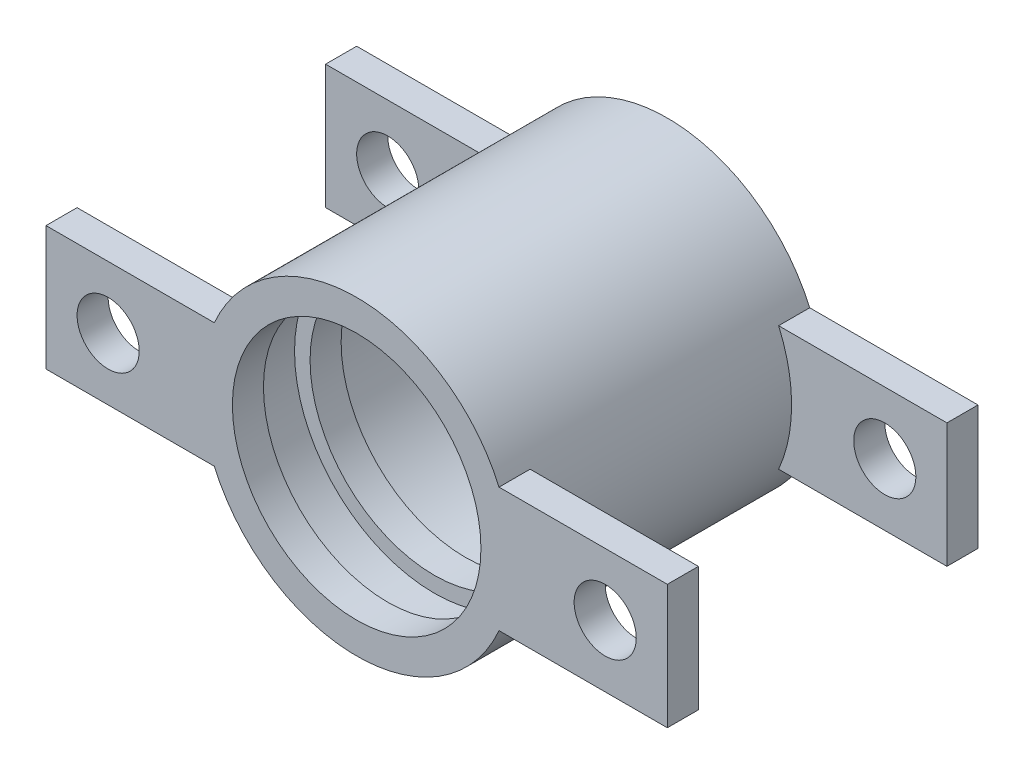
SolidWorks part; units mm, degrees
ref_plane "Front Plane" through (0, 0, 0) normal (0, 0, 1) x (1, 0, 0)
ref_plane "Top Plane" through (0, 0, 0) normal (0, 1, 0) x (1, 0, 0)
ref_plane "Right Plane" through (0, 0, 0) normal (1, 0, 0) x (0, 0, -1)
sketch "Sketch1" plane through (0, 0, 0) normal (0, 1, 0) x (1, 0, 0)
  line L0 (0, 100.9124) -> (0, -95.438) construction
  line L1 (-180.6569, 0) -> (215.3285, 0) construction
  line L2 (-50, 50) -> (-50, -50)
  line L3 (-50, -50) -> (-45, -50)
  line L5 (-45, 50) -> (-50, 50)
  line L7 (-45, -50) -> (-40, -50)
  line L8 (-45, 50) -> (-40, 50)
  line L10 (-45, 40) -> (-40, 40)
  line L11 (-40, 50) -> (-40, 40)
  line L12 (-40, -40) -> (-40, -50)
  line L13 (-45, -40) -> (-40, -40)
  line L14 (-45, 40) -> (-45, 25)
  line L15 (-45, 25) -> (-40, 25)
  line L17 (-45, 15) -> (-40, 15)
  line L18 (-40, 25) -> (-40, 15)
  line L19 (-45, -15) -> (-40, -15)
  line L21 (-45, -25) -> (-40, -25)
  line L22 (-40, -15) -> (-40, -25)
  line L23 (-45, 15) -> (-45, -15)
  line L24 (-45, -25) -> (-45, -40)
  point P14 (-42.5, 50)
  dimension "D1" = 100
  dimension "D2" = 5
  dimension "D3" = 10
  dimension "D5" = 10
  dimension "D6" = 10
  dimension "D7" = 5
  dimension "D8" = 5
  dimension "D9" = 30
  dimension "D10" = 15
  dimension "D11" = 40
  dimension "D4" = 2
revolve "Revolve1" add sketch "Sketch1" angle 360 about L0
sketch "Sketch2" plane through (0, 0, 50) normal (0, 0, 1) x (1, 0, 0)
  line L0 (0, 56.0052) -> (0, -53.8296) construction
  line L1 (45.8258, 20) -> (100, 20)
  line L3 (45.8258, -20) -> (100, -20)
  line L4 (100, 20) -> (100, -20)
  line L5 (-100, 20) -> (-100, -20)
  line L6 (-45.8258, -20) -> (-100, -20)
  line L7 (-45.8258, 20) -> (-100, 20)
  circle A0 centre (0, 0) radius 50 construction
  arc A1 (-45.8258, 20) -> (-45.8258, -20) centre (0, 0) ccw
  circle A2 centre (-80, 0) radius 10
  circle A3 centre (80, 0) radius 10
  arc A4 (45.8258, -20) -> (45.8258, 20) centre (0, 0) ccw
  point P3 (50, 0)
  dimension "D3" = 20
  dimension "D4" = 20
  dimension "D1" = 40
  dimension "D2" = 50
  dimension "D5" = 160
  dimension "D6" = 80
extrude "Boss-Extrude1" add sketch "Sketch2" against normal blind 10
ref_plane "Plane1" through (0, 0, 0) normal (0, 0, 1) x (1, 0, 0)
mirror "Mirror1" about plane through (0, 0, 0) normal (0, 0, 1) of "Boss-Extrude1"
